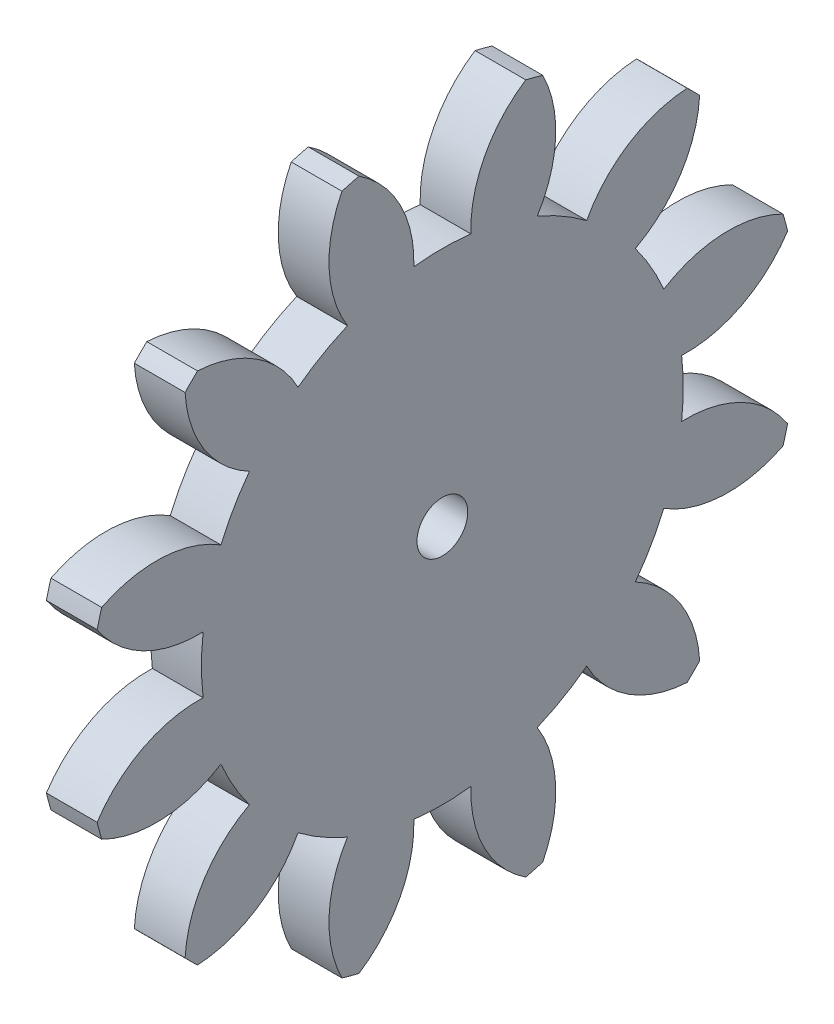
SolidWorks part; units mm, degrees
ref_plane "Plane1" through (0, 0, 0) normal (0, 0, 1) x (1, 0, 0)
ref_plane "Plane2" through (0, 0, 0) normal (0, 1, 0) x (1, 0, 0)
ref_plane "Plane3" through (0, 0, 0) normal (1, 0, 0) x (0, 0, -1)
sketch "HoldingSke" plane through (0, 0, 0) normal (0, 1, 0) x (1, 0, 0)
  line L0 (0, 0) -> (0.9781, -0.2079)
  line L1 (-15, 0) -> (100, 0) construction
  line L2 (0, 0) -> (-2.1039, 2.3779)
  line L3 (0, 0) -> (-11.863, 4.5341)
  line L4 (0, 0) -> (8.4473, 1.7955)
  line L5 (0, 0) -> (-46.8476, -17.4728)
  line L6 (0, 0) -> (-0.829, -0.5593)
  line L7 (-2.1039, 2.3779) -> (8.6586, 51.2059)
  line L8 (-76.2, 54.61) -> (-76.1, 54.61)
  line L9 (-71.009, 38.7566) -> (-53.1078, 45.2721)
  line L10 (-76.2, 71.12) -> (104.1128, 71.12)
  line L11 (0, 0) -> (-1, 0)
  line L12 (-76.2, 101.6) -> (-76.162, 101.6)
  line L13 (24.9733, 27.94) -> (52.9518, 28.4284)
  line L14 (24.9733, 27.94) -> (24.9743, 27.94)
  line L15 (24.9733, 27.94) -> (100.4006, 29.5858)
  line L16 (-63.627, -1) -> (-12.827, -1)
  circle A0 centre (0, 0) radius 0.5
  circle A1 centre (0, 0) radius 4.749
  circle A2 centre (0, 0) radius 37.5
  circle A3 centre (0, 0) radius 0.5
  dimension "MHD" = 9.498
  dimension "Hub_dia" = 75
  dimension "Bore" = 1
  dimension "MBD" = 1
  dimension "Num_teeth" = 12
  dimension "Pitch" = 1
  dimension "Overall_len" = 50
  dimension "Show_teeth" = 12
  dimension "Thickness" = 1
  dimension "OAL" = 50.0001
  dimension "T_dim" = 0.1
  dimension "Ap" = 20
  dimension "H" = 19.05
  dimension "Pitch_radius" = 180.3128
  dimension "Width" = 1
  dimension "Backlash" = 0.038
  dimension "Addendum_fac" = 1
  dimension "Dedendum_fac" = 1.25
  dimension "Clearance_fac" = 0.25
  dimension "Dedendum_add" = 0.001
  dimension "Module" = 1
sketch "BasProSke" plane through (0, 0, 0) normal (0, 1, 0) x (1, 0, 0)
  line L0 (-10, 0) -> (60, 0) construction
  line L1 (0, 0) -> (0, 7)
  line L2 (0, 0) -> (1, 0)
  line L3 (1, 0) -> (1, 7)
  line L4 (1, 7) -> (0, 7)
  dimension "Thickness" = 1
  dimension "Diameter" = 14
revolve "Base-Revolve" add sketch "BasProSke" angle 360 about L0
sketch "TooCutSke" plane through (0, 0, 0) normal (1, 0, 0) x (0, 0, -1)
  line L1 (0, 0) -> (0, 107) construction
  line L2 (0, 0) -> (-0.8496, 5.9395) construction
  line L3 (0, 0) -> (-3.0836, 11.5081) construction
  line L4 (-0.8496, 5.9395) -> (-1.5418, 5.7541) construction
  arc A0 (0.5622, 4.7156) -> (-0.5622, 4.7156) centre (0, 0) ccw
  arc A1 (1.6729, 6.8233) -> (-1.6729, 6.8233) centre (0, 0) ccw
  circle A2 centre (0, 0) radius 6 construction
  circle A3 centre (0, 0) radius 5.6382 construction
  arc A4 (-0.5622, 4.7156) -> (-1.6729, 6.8233) centre (-2.9608, 4.7982) ccw
  arc A5 (1.6729, 6.8233) -> (0.5622, 4.7156) centre (2.9608, 4.7982) ccw
  dimension "Root_dia" = 9.498
  dimension "Overcut_dia" = 14.0508
  dimension "Pitch_dia" = 12
  dimension "Base_dia" = 11.2763
  dimension "Flank_rad" = 2.4
  dimension "Half_ang" = 15
  dimension "Half_CT" = 0.7167
extrude "ToothCut" cut sketch "TooCutSke" along normal through all
fillet "Breaks" [suppressed] radius 0.02
fillet "RootFillets" [suppressed] radius 0.251
pattern_circular "TeethCuts" count 12 every 30 about axis through (-10, 0, 0) along (1, 0, 0) of "ToothCut", "RootFillets", "Breaks"
sketch "HubNeaOneSke" plane through (0, 0, 0) normal (-1, 0, 0) x (0, 0, 1)
  circle A0 centre (0, 0) radius 4.749
  dimension "Diameter" = 9.498
extrude "HubNearOne" [suppressed] add sketch "HubNeaOneSke" along normal blind 49.0001
sketch "HubNeaBotSke" plane through (0, 0, 0) normal (-1, 0, 0) x (0, 0, 1)
  circle A0 centre (0, 0) radius 4.749
  dimension "Diameter" = 9.498
extrude "HubNearBoth" [suppressed] add sketch "HubNeaBotSke" along normal blind 24.5
ref_plane "FarPln" through (1, 0, 0) normal (1, 0, 0) x (0, 0, -1)
sketch "HubFarSke" plane through (1, 0, 0) normal (1, 0, 0) x (0, 0, -1)
  circle A0 centre (0, 0) radius 4.749
  dimension "Diameter" = 9.498
extrude "HubFar" [suppressed] add sketch "HubFarSke" along normal blind 24.5
sketch "BorSke" plane through (0, 0, 0) normal (1, 0, 0) x (0, 0, -1)
  circle A0 centre (0, 0) radius 0.5
  dimension "Diameter" = 1
extrude "Bore" cut sketch "BorSke" along normal mid plane 100.0001
sketch "KeySke" plane through (0, 0, 0) normal (1, 0, 0) x (0, 0, -1)
  line L0 (-0.05, 0) -> (-0.05, 0.6)
  line L1 (-0.05, 0.6) -> (0.05, 0.6)
  line L2 (0.05, 0.6) -> (0.05, 0)
  line L3 (0, 0) -> (0, 34) construction
  line L4 (-0.05, 0) -> (0.05, 0)
  dimension "Offset" = 0.6
extrude "Keyway" [suppressed] cut sketch "KeySke" along normal mid plane 100.0001
pattern_circular "Keyway2" [suppressed] count 2 every 90 about axis through (-10, 0, 0) along (1, 0, 0)
equation "' \"Module@HoldingSke\" = 6.35"
equation "' \"Num_teeth@HoldingSke\" = 12"
equation "' \"Ap@HoldingSke\" =  20"
equation "' \"Ap@HoldingSke\" = 20"
equation "' \"Width@HoldingSke\" = 0.5 * 25.4"
equation "' \"Hub_dia@HoldingSke\"= 1 * 25.4"
equation "' \"Hub_dia@HoldingSke\" = 1 * 25.4"
equation "' \"Overall_len@HoldingSke\" = 1.0 * 25.4"
equation "' \"Bore@HoldingSke\" = 0.75 * 25.4"
equation "' \"T_dim@HoldingSke\" = 0.1 * 25.4"
equation "' \"Width@KeySke\" = 0.25 * 25.4"
equation "' \"Show_teeth@HoldingSke\" = 13"
equation "' \"Backlash@HoldingSke\" = 0.009 * 25.4"
equation "' \"Addendum_fac@HoldingSke\" = 1.0"
equation "' \"Dedendum_fac@HoldingSke\" = 1.25"
equation "' \"Dedendum_add@HoldingSke\" = 0.00005 * 25.4"
equation "' \"Clearance_fac@HoldingSke\" = 0.25"
equation "\"Pitch@HoldingSke\" = 1 / \"Module@HoldingSke\""
equation "\"Overcut_dia@TooCutSke\" = (\"Num_teeth@HoldingSke\" + 2 * \"Addendum_fac@HoldingSke\") / \"Pitch@HoldingSke\" + 0.002 * 25.4"
equation "\"Pitch_dia@TooCutSke\" = \"Num_teeth@HoldingSke\" / \"Pitch@HoldingSke\""
equation "\"Base_dia@TooCutSke\" = \"Num_teeth@HoldingSke\" / \"Pitch@HoldingSke\" * cos((\"Ap@HoldingSke\"  * 3.14159265 / 180))"
equation "\"Root_dia@TooCutSke\" = (\"Num_teeth@HoldingSke\" + 2) / \"Pitch@HoldingSke\" - 2 * (\"Addendum_fac@HoldingSke\" + \"Dedendum_fac@HoldingSke\") / \"Pitch@HoldingSke\" - \"Dedendum_add@HoldingSke\" * 2"
equation "\"Half_ang@TooCutSke\" = 180 / \"Num_teeth@HoldingSke\""
equation "\"Half_CT@TooCutSke\" = \"Num_teeth@HoldingSke\" / \"Pitch@HoldingSke\" * sin((3.14159265 / 2 / \"Num_teeth@HoldingSke\")) / 2 - 7 * \"Backlash@HoldingSke\" / 4"
equation "\"Flank_rad@TooCutSke\" = \"Num_teeth@HoldingSke\" / \"Pitch@HoldingSke\" / 5"
equation "\"Radius@RootFillets\" = \"Clearance_fac@HoldingSke\" / \"Pitch@HoldingSke\" + \"Dedendum_add@HoldingSke\""
equation "\"Break_rad@Breaks\" = 0.02 / \"Pitch@HoldingSke\""
equation "\"Thickness@HoldingSke\" = \"Width@HoldingSke\""
equation "\"OAL@HoldingSke\" = \"Thickness@HoldingSke\""
equation "\"MHD@HoldingSke\" = (\"Num_teeth@HoldingSke\" + 2) / \"Pitch@HoldingSke\" - 2 * (\"Addendum_fac@HoldingSke\" + \"Dedendum_fac@HoldingSke\")  / \"Pitch@HoldingSke\" - \"Dedendum_add@HoldingSke\" * 2"
equation "\"MBD@HoldingSke\" = (\"Num_teeth@HoldingSke\" + 2) / \"Pitch@HoldingSke\" - 2 * (\"Addendum_fac@HoldingSke\" + \"Dedendum_fac@HoldingSke\")  / \"Pitch@HoldingSke\" - \"Dedendum_add@HoldingSke\" * 2 - 0.002 * 25.4"
equation "\"MHD@HoldingSke\" = ((sgn( \"MHD@HoldingSke\" - \"Hub_dia@HoldingSke\" )-1)*( \"MHD@HoldingSke\" - \"Hub_dia@HoldingSke\" ))/-2+ \"Hub_dia@HoldingSke\""
equation "\"MBD@HoldingSke\" = ((sgn( \"MBD@HoldingSke\" - \"Bore@HoldingSke\" )-1)*( \"MBD@HoldingSke\" - \"Bore@HoldingSke\" ))/-2+ \"Bore@HoldingSke\""
equation "\"OAL@HoldingSke\" = ((sgn( \"OAL@HoldingSke\" - \"Overall_len@HoldingSke\" )+1)*( \"OAL@HoldingSke\" - \"Overall_len@HoldingSke\" ))/2 + \"Overall_len@HoldingSke\" + 0.000002 * 25.4"
equation "\"Num_teeth@TeethCuts\" = int( \"Show_teeth@HoldingSke\" ) + 1"
equation "\"Num_teeth@TeethCuts\" = ((sgn( \"Num_teeth@TeethCuts\" - \"Num_teeth@HoldingSke\" )-1)*( \"Num_teeth@TeethCuts\" - \"Num_teeth@HoldingSke\" ))/-2+ \"Num_teeth@HoldingSke\""
equation "\"Num_teeth@TeethCuts\" = ((sgn( \"Num_teeth@TeethCuts\" - 2.0)+1)*( \"Num_teeth@TeethCuts\" - 2.0))/2 +2.0"
equation "\"Angle@TeethCuts\" = 360.0 / \"Num_teeth@HoldingSke\""
equation "\"Diameter@BasProSke\" = (\"Num_teeth@HoldingSke\" + 2 * \"Addendum_fac@HoldingSke\") / \"Pitch@HoldingSke\""
equation "\"Thickness@BasProSke\"  = \"Thickness@HoldingSke\""
equation "' \"Fillet_rad@BasProSke\" =  \"Thickness@HoldingSke\" * 0.05"
equation "' \"Fillet_rad@BasProSke\" = \"Thickness@HoldingSke\" * 0.05"
equation "\"MHD@HoldingSke\" = ((sgn( \"MHD@HoldingSke\" - \"Root_dia@TooCutSke\" )-1)*( \"MHD@HoldingSke\" - \"Root_dia@TooCutSke\" ))/-2+ \"Root_dia@TooCutSke\""
equation "\"Diameter@HubNeaOneSke\" = \"MHD@HoldingSke\""
equation "\"Length@HubNearOne\" = \"OAL@HoldingSke\" - \"Thickness@BasProSke\""
equation "\"Diameter@HubNeaBotSke\" = \"MHD@HoldingSke\""
equation "\"Length@HubNearBoth\" = ( \"OAL@HoldingSke\" - \"Thickness@BasProSke\" ) / 2.0"
equation "\"Thickness@FarPln\" = \"Thickness@BasProSke\""
equation "\"Diameter@HubFarSke\" = \"MHD@HoldingSke\""
equation "\"Length@HubFar\" = ( \"OAL@HoldingSke\" - \"Thickness@BasProSke\" ) / 2.0"
equation "\"Diameter@BorSke\" = \"MBD@HoldingSke\""
equation "\"D1@Bore\" = \"OAL@HoldingSke\" * 2.0"
equation "\"D1@Keyway\" = \"OAL@HoldingSke\" * 2.0"
equation "\"Offset@KeySke\" = \"T_dim@HoldingSke\" + \"MBD@HoldingSke\" / 2.0"
